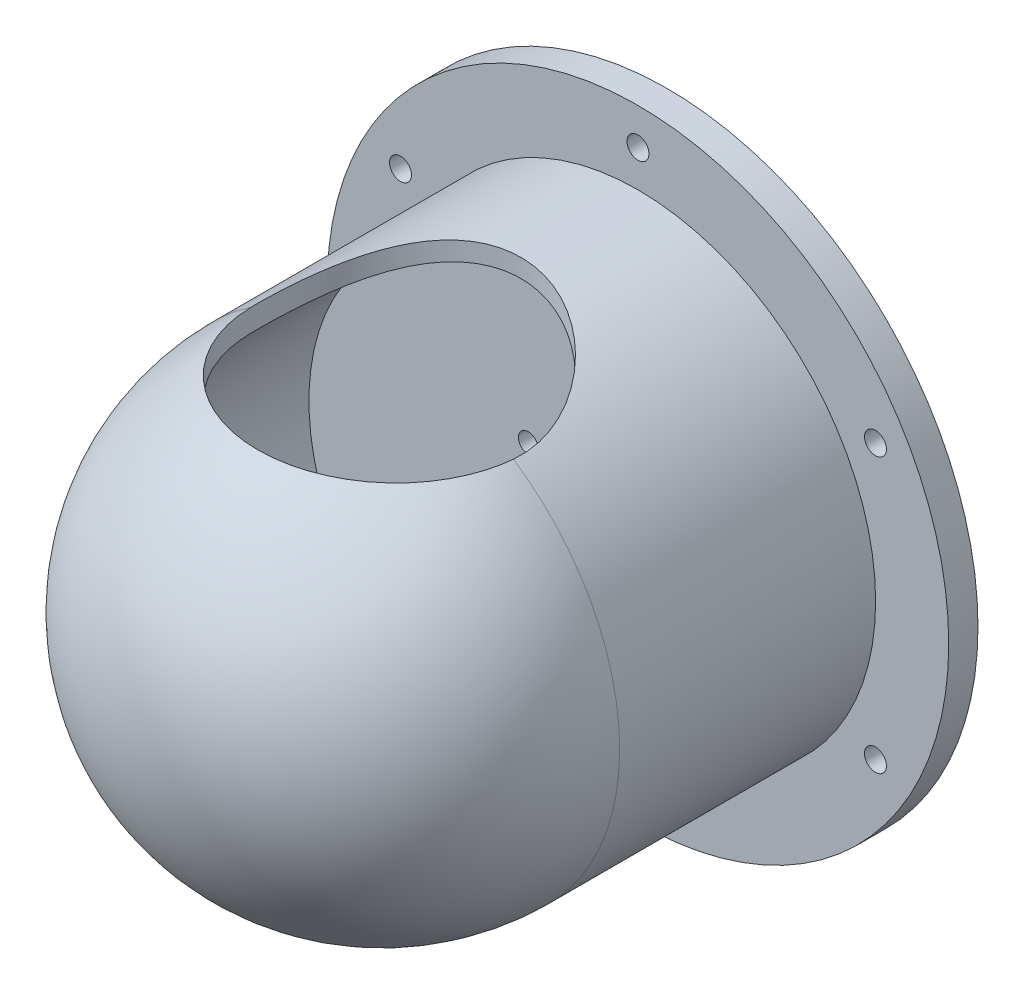
SolidWorks part; units mm, degrees
ref_plane "前视基准面" through (0, 0, 0) normal (0, 0, 1) x (1, 0, 0)
ref_plane "上视基准面" through (0, 0, 0) normal (0, 1, 0) x (1, 0, 0)
ref_plane "右视基准面" through (0, 0, 0) normal (1, 0, 0) x (0, 0, -1)
other "Configuration Table"
sketch "草图1" plane through (0, 0, 0) normal (1, 0, 0) x (0, 0, -1)
  line L2 (3.3172, 159.6258) -> (43.3172, 159.6258)
  line L3 (-56.6828, 94.6258) -> (-61.6828, 94.6258)
  line L4 (3.3172, 154.6258) -> (43.3172, 154.6258)
  line L5 (43.3172, 154.6258) -> (43.3172, 94.6258)
  line L6 (43.3172, 159.6258) -> (73.3172, 159.6258)
  line L8 (73.3172, 159.6258) -> (73.3172, 179.6258)
  line L9 (73.3172, 179.6258) -> (81.3172, 179.6258)
  line L10 (81.3172, 179.6258) -> (81.3172, 154.6258)
  line L13 (43.3172, 94.6258) -> (53.3172, 94.6258)
  line L14 (53.3172, 94.6258) -> (53.3172, 154.6258)
  line L15 (53.3172, 154.6258) -> (73.3172, 154.6258)
  line L16 (73.3172, 154.6258) -> (81.3172, 154.6258)
  arc A0 (3.3172, 154.6258) -> (-56.6828, 94.6258) centre (3.3172, 94.6258) ccw
  arc A1 (-61.6828, 94.6258) -> (3.3172, 159.6258) centre (3.3172, 94.6258) cw
  dimension "D1" = 100
  dimension "D2" = 138
revolve "旋转6" add sketch "草图1" angle 360 about L13
sketch "草图5" plane through (0, 0, 0) normal (0, 1, 0) x (1, 0, 0)
  line L5 (0, 3.3172) -> (0, 5.3172)
  line L6 (65, 3.3172) -> (-65, 3.3172) construction
  circle A0 centre (0, 5.3172) radius 36
extrude "切除-拉伸1" cut sketch "草图5" along normal blind 191
sketch "草图6" plane through (0, 0, 0) normal (0, 0, 1) x (1, 0, 0)
  line L2 (0, 166.6258) -> (0, 169.6258)
  line L3 (62.3538, 130.6258) -> (64.9519, 132.1258)
  line L4 (62.3538, 58.6258) -> (64.9519, 57.1258)
  line L5 (-62.3538, 130.6258) -> (-64.9519, 132.1258)
  line L6 (-62.3538, 58.6258) -> (-64.9519, 57.1258)
  circle A0 centre (0, 169.6258) radius 3
  circle A1 centre (0, 19.6258) radius 3
  circle A2 centre (64.9519, 132.1258) radius 3
  circle A3 centre (64.9519, 57.1258) radius 3
  circle A4 centre (-64.9519, 132.1258) radius 3
  circle A5 centre (-64.9519, 57.1258) radius 3
  dimension "D1" = 6
extrude "切除-拉伸3" cut sketch "草图6" against normal blind 225
sketch "草图7" plane through (0, 0, 0) normal (0, 0, 1) x (1, 0, 0)
  circle A0 centre (0, 94.3862) radius 2.7
  circle A1 centre (0, 114.6258) radius 2.7
  circle A2 centre (0, 74.3862) radius 2.7
extrude "切除-拉伸4" cut sketch "草图7" against normal blind 111 contours A1 | A0 | A2
